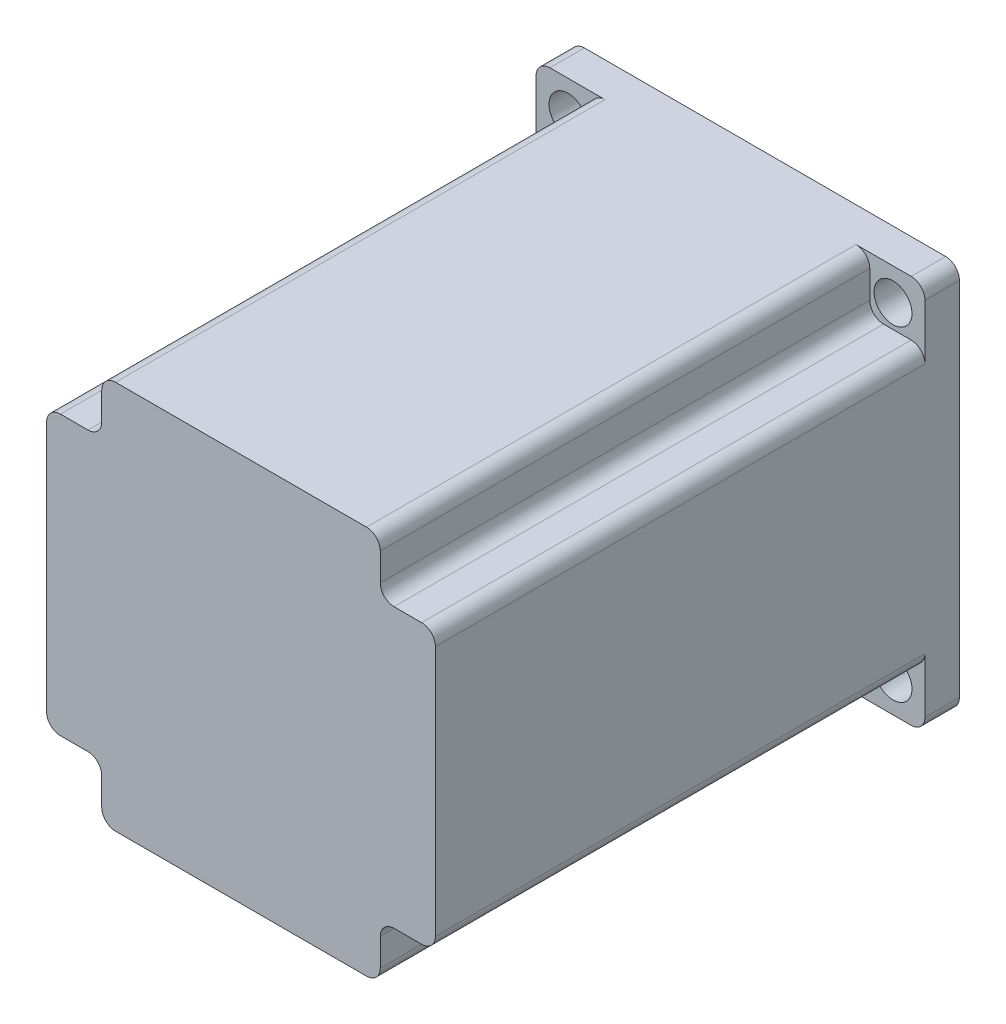
SolidWorks part; units mm, degrees
ref_plane "Front Plane" through (0, 0, 0) normal (0, 0, 1) x (1, 0, 0)
ref_plane "Top Plane" through (0, 0, 0) normal (0, 1, 0) x (1, 0, 0)
ref_plane "Right Plane" through (0, 0, 0) normal (1, 0, 0) x (0, 0, -1)
ref_plane "Plane1"
sketch "Sketch1" plane through (0, 0, 0) normal (0, 0, 1) x (1, 0, 0)
  line L0 (-28.2, -28.2) -> (28.2, -28.2)
  line L1 (28.2, -28.2) -> (28.2, 28.2)
  line L2 (28.2, 28.2) -> (-28.2, 28.2)
  line L3 (-28.2, 28.2) -> (-28.2, -28.2)
  dimension "D1" = 56.4
  dimension "D2" = 56.4
extrude "Extrusion1" add sketch "Sketch1" along normal blind 76
hole_wizard "Thread4" positions "Sketch3" profile "Sketch2" legacy
sketch "Sketch3" plane through (0, 0, 0) normal (0, 0, -1) x (-1, 0, 0)
  point P1 (-23.57, 23.57)
  point P2 (23.57, 23.57)
  point P3 (23.57, -23.57)
  point P4 (-23.57, -23.57)
sketch "Sketch2" plane through (23.57, 23.57, 0) normal (1, 0, 0) x (0, 1, 0)
  line L0 (0, 0) -> (0, 9.6524)
  line L1 (0, 9.6524) -> (2.75, 8)
  line L2 (2.75, 8) -> (2.75, 0)
  line L4 (2.75, 0) -> (0, 0)
  line L6 (0, 9.6524) -> (-2.75, 8) construction
  line L7 (0, -4.2442) -> (0, 117.3081) construction
  dimension "Diameter" = 5.5
  dimension "Depth" = 8
  dimension "Drill Angle" = 118
cosmetic thread "Cosmetic Thread1"
cosmetic thread "Cosmetic Thread2"
cosmetic thread "Cosmetic Thread3"
cosmetic thread "Cosmetic Thread4"
sketch "Sketch4" plane through (0, 0, 0) normal (0, 0, -1) x (-1, 0, 0)
  circle A0 centre (0, 0) radius 19.05
  dimension "D1" = 38.1
extrude "Extrusion2" add sketch "Sketch4" along normal blind 1.6
sketch "Sketch5" plane through (0, 0, -1.6) normal (0, 0, -1) x (-1, 0, 0)
  circle A0 centre (0, 0) radius 3.175
  dimension "D1" = 6.35
extrude "Extrusion3" add sketch "Sketch5" along normal blind 21
sketch "Sketch6" plane through (0, 0, 76) normal (0, 0, 1) x (1, 0, 0)
  line L0 (-28.2, -28.2) -> (-20.2, -28.2)
  line L1 (-20.2, -28.2) -> (-20.2, -20.2)
  line L2 (-20.2, -20.2) -> (-28.2, -20.2)
  line L3 (-28.2, -20.2) -> (-28.2, -28.2)
  line L4 (28.2, -28.2) -> (28.2, -20.2)
  line L5 (28.2, -20.2) -> (20.2, -20.2)
  line L6 (20.2, -20.2) -> (20.2, -28.2)
  line L7 (20.2, -28.2) -> (28.2, -28.2)
  line L8 (28.2, 28.2) -> (20.2, 28.2)
  line L9 (20.2, 28.2) -> (20.2, 20.2)
  line L10 (20.2, 20.2) -> (28.2, 20.2)
  line L11 (28.2, 20.2) -> (28.2, 28.2)
  line L12 (-28.2, 28.2) -> (-28.2, 20.2)
  line L13 (-28.2, 20.2) -> (-20.2, 20.2)
  line L14 (-20.2, 20.2) -> (-20.2, 28.2)
  line L15 (-20.2, 28.2) -> (-28.2, 28.2)
  line M1 (-28.2, 28.2) -> (-28.2, -28.2)
  line M2 (-28.2, -28.2) -> (28.2, -28.2)
  line M3 (28.2, -28.2) -> (28.2, 28.2)
  line M4 (28.2, 28.2) -> (-28.2, 28.2)
  dimension "D1" = 8
  dimension "D2" = 8
  dimension "D3" = 8
  dimension "D4" = 8
  dimension "D5" = 8
  dimension "D6" = 8
  dimension "D7" = 8
  dimension "D8" = 8
extrude "Extrusion4" cut sketch "Sketch6" against normal blind 71 contours L1 L2 M1 M2 | L5 L6 M2 M3 | L9 L10 M3 M4 | L13 L14 M4 M1
fillet "Fillet1" radius 2 1 edges at (-28.2, 28.2, 2.5)
fillet "Fillet2" radius 2 15 edges at (-20.2, -20.2, 40.5) (-20.2, -28.2, 40.5) (28.2, -28.2, 2.5) (28.2, -20.2, 40.5) (20.2, -20.2, 40.5) (20.2, -28.2, 40.5) (28.2, 20.2, 40.5) (20.2, 20.2, 40.5) (20.2, 28.2, 40.5) (-28.2, -28.2, 2.5) (-28.2, -20.2, 40.5) (-20.2, 20.2, 40.5) (-28.2, 20.2, 40.5) (-20.2, 28.2, 40.5) (28.2, 28.2, 2.5)
